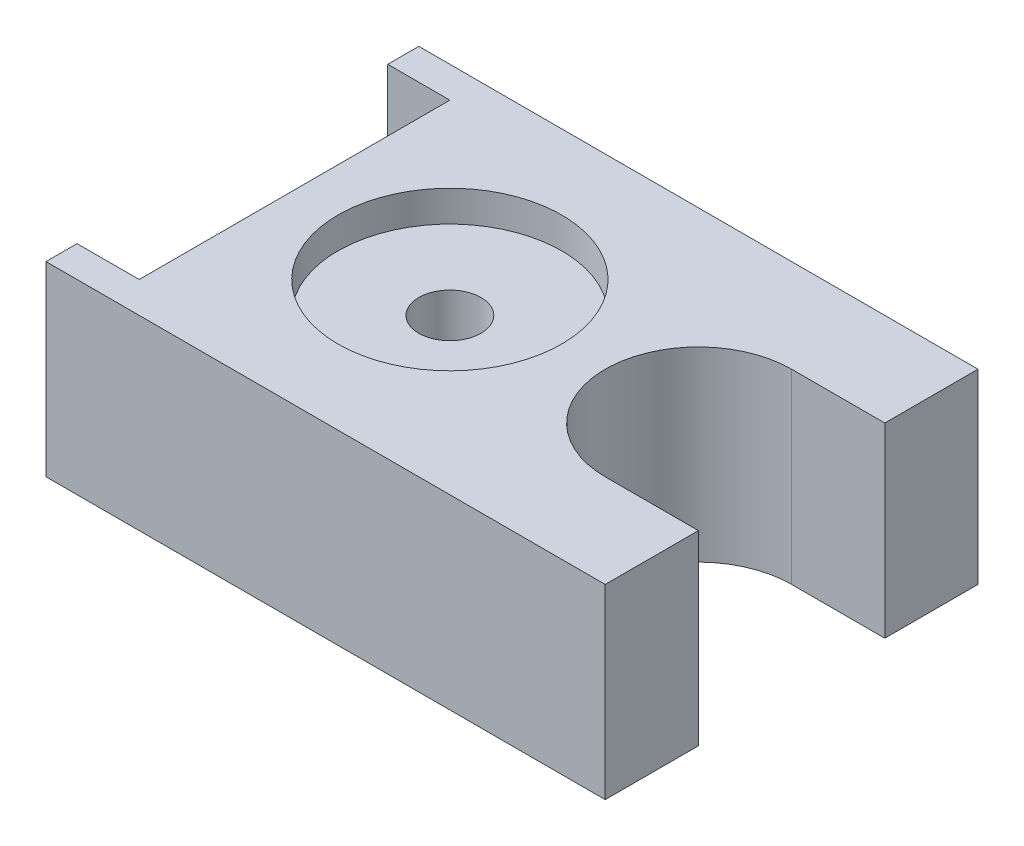
SolidWorks part; units mm, degrees
ref_plane "Plano frontal" through (0, 0, 0) normal (0, 0, 1) x (1, 0, 0)
ref_plane "Plano superior" through (0, 0, 0) normal (0, 1, 0) x (1, 0, 0)
ref_plane "Plano direito" through (0, 0, 0) normal (1, 0, 0) x (0, 0, -1)
sketch "Esboço1" plane through (0, 0, 0) normal (0, 1, 0) x (1, 0, 0)
  line L0 (0, 0) -> (90, 0)
  line L1 (90, 0) -> (90, 60)
  line L2 (90, 60) -> (0, 60)
  line L3 (0, 60) -> (0, 0)
  dimension "D1" = 90
  dimension "D2" = 60
extrude "Ressalto-extrusão1" add sketch "Esboço1" along normal blind 30
sketch "Esboço2" plane through (0, 30, 0) normal (0, 1, 0) x (1, 0, 0)
  line L0 (90, 45) -> (75, 45)
  line L1 (90, 0) -> (90, 60) construction
  line L2 (75, 15) -> (90, 15)
  line L3 (90, 15) -> (90, 45)
  line L4 (0, 0) -> (90, 0) construction
  arc A0 (75, 45) -> (75, 15) centre (75, 30) ccw
  point P6 (82.5, 15)
  dimension "D1" = 30
  dimension "D2" = 15
  dimension "D3" = 15
extrude "Corte-extrusão1" cut sketch "Esboço2" against normal through all
sketch "Esboço18" plane through (0, 0, 0) normal (-1, 0, 0) x (0, 0, 1)
  line L0 (-55, 30) -> (-55, 0)
  line L1 (-60, 30) -> (0, 30) construction
  line L2 (-60, 0) -> (0, 0) construction
  line L3 (-55, 0) -> (-5, 0)
  line L4 (-5, 0) -> (-5, 30)
  line L5 (-5, 30) -> (-55, 30)
  line L6 (0, 30) -> (0, 0) construction
  dimension "D1" = 50
  dimension "D2" = 5
extrude "Corte-extrusão2" cut sketch "Esboço18" against normal blind 10
sketch "Esboço20" plane through (0, 30, 0) normal (0, 1, 0) x (1, 0, 0)
  line L3 (10, 5) -> (10, 55) construction
  line L4 (90, 60) -> (0, 60) construction
  circle A0 centre (35, 30) radius 18
  circle A4 centre (35, 30) radius 5
  point P0 (35, 30)
  dimension "D1" = 25
  dimension "D2" = 30
  dimension "D3" = 36
  dimension "D4" = 10
extrude "Corte-extrusão4" cut sketch "Esboço20" against normal through all contours A4
sketch "Esboço22" plane through (0, 30, 0) normal (0, 1, 0) x (1, 0, 0)
  circle A0 centre (35, 30) radius 18
  dimension "D1" = 36
extrude "Corte-extrusão5" cut sketch "Esboço22" against normal blind 5
